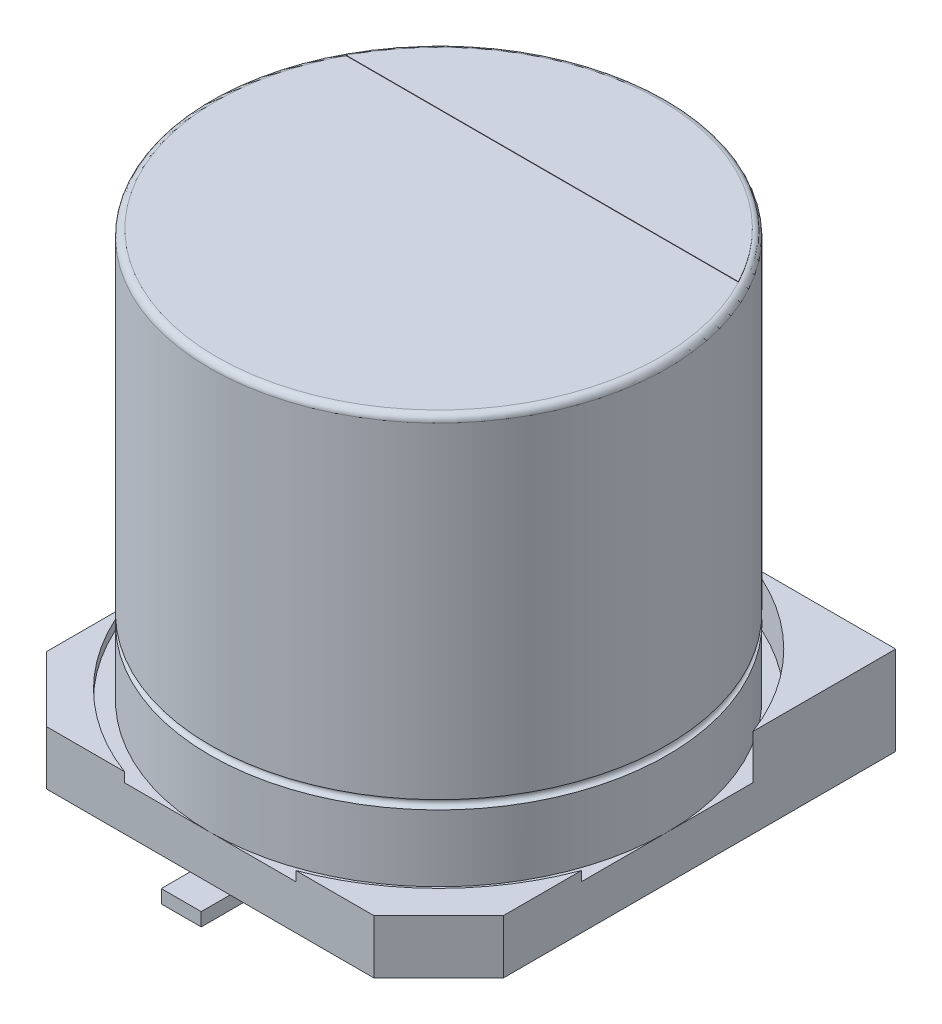
SolidWorks part; units mm, degrees
ref_plane "Front Plane" through (0, 0, 0) normal (0, 0, 1) x (1, 0, 0)
ref_plane "Top Plane" through (0, 0, 0) normal (0, 1, 0) x (1, 0, 0)
ref_plane "Right Plane" through (0, 0, 0) normal (1, 0, 0) x (0, 0, -1)
sketch "Sketch1" plane through (0, 0, 0) normal (0, 1, 0) x (1, 0, 0)
  line L0 (-5.15, 5.15) -> (5.15, 5.15)
  line L1 (5.15, 5.15) -> (5.15, -3.6912)
  line L2 (5.15, -3.6912) -> (3.6912, -5.15)
  line L3 (3.6912, -5.15) -> (-3.6912, -5.15)
  line L4 (-3.6912, -5.15) -> (-5.15, -3.6912)
  line L5 (-5.15, -3.6912) -> (-5.15, 5.15)
  line L6 (0, 5.1629) -> (0, -6.366) construction
  line L7 (-5.4826, 0) -> (5.3839, 0) construction
  point P11 (0, 0)
  point P12 (0, -5.15)
  point P13 (-2.0536, -5.15)
  point P14 (5.15, -3.3153)
  point P15 (5.15, -3.6912)
  dimension "D1" = 10.3
  dimension "D2" = 10.3
extrude "Boss-Extrude1" add sketch "Sketch1" along normal blind 2
sketch "Sketch2" plane through (0, 2, 0) normal (0, 1, 0) x (1, 0, 0)
  circle A0 centre (0, 0) radius 5.5
  dimension "D1" = 11
extrude "Cut-Extrude1" cut sketch "Sketch2" against normal blind 1
sketch "Sketch8" plane through (-5.15, 0, 0) normal (-1, 0, 0) x (0, 0, 1)
  line L1 (0.9165, 1.2174) -> (5.9, 1.2174)
  line L2 (0.9165, 1.2174) -> (0.9165, 2.8185)
  line L3 (0.9165, 2.8185) -> (5.9, 2.8185)
  line L4 (5.9, 1.2174) -> (5.9, 2.8185)
extrude "Cut-Extrude4" cut sketch "Sketch8" against normal up to surface (10.3 mm away)
sketch "Sketch5" plane through (0, 0, 0) normal (0, 0, 1) x (1, 0, 0)
  line L0 (0, 1) -> (0, 10.407) construction
  line L2 (0, 1) -> (-5.15, 1)
  line L3 (-5.15, 1) -> (-5.15, 2.5)
  line L4 (-5.15, 2.7) -> (-5.15, 10.05)
  line L5 (-5, 10.2) -> (0, 10.2)
  line L6 (0, 10.2) -> (0, 1)
  arc A0 (-5.15, 2.5) -> (-5.15, 2.7) centre (-5.15, 2.6) ccw
  arc A1 (-5.15, 10.05) -> (-5, 10.2) centre (-5, 10.05) cw
  dimension "D1" = 0.1
  dimension "D4" = 0.15
  dimension "D2" = 9.2
  dimension "D3" = 1.5
  dimension "D5" = 5
revolve "Revolve1" add sketch "Sketch5" angle 360 about L6
sketch "Sketch6" plane through (0, 10.2, 0) normal (0, 1, 0) x (1, 0, 0)
  line L0 (-4.4203, 2.3369) -> (4.4203, 2.3369)
  circle A0 centre (0, 0) radius 5 construction
  arc A1 (4.4203, 2.3369) -> (-4.4203, 2.3369) centre (0, 0) ccw
extrude "Boss-Extrude4" add sketch "Sketch6" along normal blind 0.01
sketch "Sketch9" plane through (0, 0, 0) normal (0, -1, 0) x (1, 0, 0)
  line L0 (0, 4.3805) -> (0, -0.5544) construction
  line L1 (4.5693, 0) -> (-4.8861, 0) construction
  line L2 (0.45, -5.8) -> (-0.45, -5.8)
  line L3 (0.45, 2.3) -> (-0.45, 2.3)
  line L4 (0.45, 2.3) -> (0.45, 5.8)
  line L5 (0.45, 5.8) -> (-0.45, 5.8)
  line L6 (-0.45, 2.3) -> (-0.45, 5.8)
  line L7 (0.45, 2.3) -> (-0.45, 5.8) construction
  line L8 (0.45, 5.8) -> (-0.45, 2.3) construction
  line L9 (-0.45, -2.3) -> (-0.45, -5.8)
  line L10 (0.45, -2.3) -> (-0.45, -2.3)
  line L11 (0.45, -2.3) -> (0.45, -5.8)
  point P5 (0, 4.05)
  dimension "D1" = 2.3
  dimension "D2" = 3.5
  dimension "D3" = 0.9
extrude "Boss-Extrude5" add sketch "Sketch9" along normal blind 0.3
